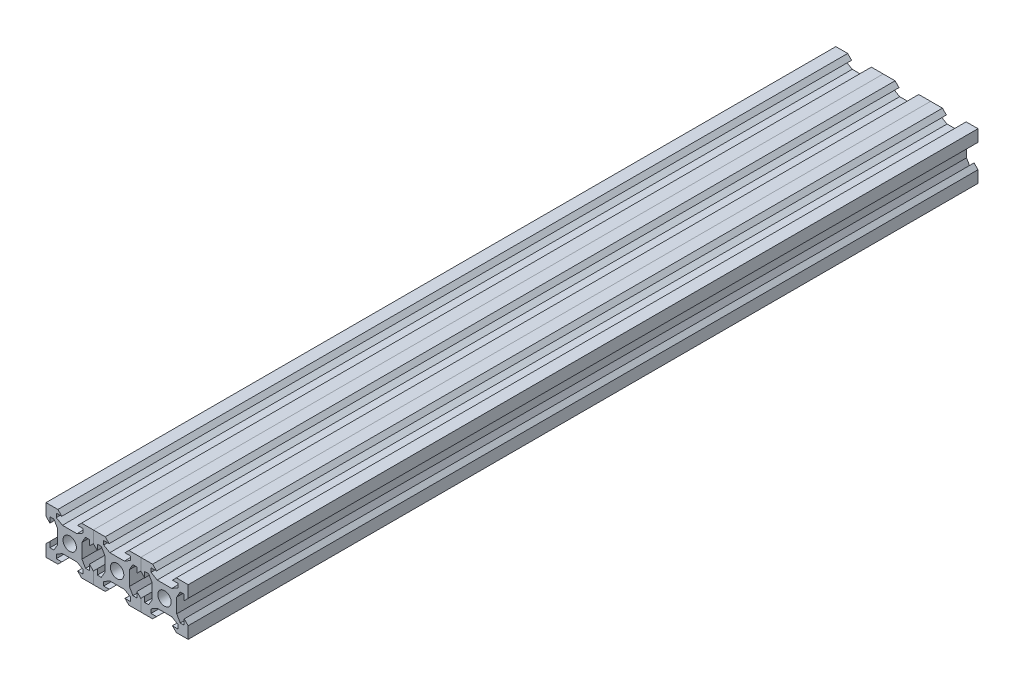
SolidWorks part; units mm, degrees
ref_plane "Alzado" through (0, 0, 0) normal (0, 0, 1) x (1, 0, 0)
ref_plane "Planta" through (0, 0, 0) normal (0, 1, 0) x (1, 0, 0)
ref_plane "Vista lateral" through (0, 0, 0) normal (1, 0, 0) x (0, 0, -1)
sketch "Sketch1" plane through (0, 0, 0) normal (0, 0, 1) x (1, 0, 0)
  line L0 (0, 0) -> (0, 50000) construction
  line L1 (45, 15) -> (-45, 15)
  line L2 (45, 15) -> (45, 7.5)
  line L3 (-45, -15) -> (-37.5, -15)
  line L4 (-45, 15) -> (-45, 7.5)
  line L5 (45, 15) -> (-45, -15) construction
  line L6 (45, -15) -> (-45, 15) construction
  line L7 (-45, -15) -> (-45, -7.5)
  line L8 (-22.5, -15) -> (-7.5, -15)
  line L9 (7.5, -15) -> (22.5, -15)
  line L10 (37.5, -15) -> (45, -15)
  line L11 (0, 0) -> (50000, 0) construction
  line L12 (30, 0) -> (30, 50000) construction
  line L13 (-30, 0) -> (-30, -50000) construction
  line L14 (-15, 7.5) -> (-15, 50007.5) construction
  line L15 (15, 7.5) -> (15, 50007.5) construction
  line L17 (45, -7.5) -> (45, -15)
  circle A0 centre (0, 0) radius 4.25
  circle A1 centre (-30, 0) radius 4.25
  circle A2 centre (30, 0) radius 4.25
  point P0 (0, 0)
  line B0 (42.5, 5) -> (42.5, 8.5)
  line B1 (42.5, 8.5) -> (40, 8.5)
  line B2 (40, 8.5) -> (37.75, 4.6029)
  line B3 (37.75, 4.6029) -> (37.75, -4.6029)
  line B4 (37.75, 0) -> (45, 0) construction
  line B5 (42.5, 5) -> (45, 7.5)
  line B6 (42.5, -5) -> (45, -7.5)
  line B7 (40, -8.5) -> (37.75, -4.6029)
  line B8 (42.5, -8.5) -> (40, -8.5)
  line B9 (42.5, -5) -> (42.5, -8.5)
  line B10 (35, -12.5) -> (38.5, -12.5)
  line B11 (38.5, -12.5) -> (38.5, -10)
  line B12 (38.5, -10) -> (34.6029, -7.75)
  line B13 (34.6029, -7.75) -> (25.3971, -7.75)
  line B14 (30, -7.75) -> (30, -15) construction
  line B15 (35, -12.5) -> (37.5, -15)
  line B16 (25, -12.5) -> (22.5, -15)
  line B17 (21.5, -10) -> (25.3971, -7.75)
  line B18 (21.5, -12.5) -> (21.5, -10)
  line B19 (25, -12.5) -> (21.5, -12.5)
  line B20 (-35, -12.5) -> (-38.5, -12.5)
  line B21 (-38.5, -12.5) -> (-38.5, -10)
  line B22 (-38.5, -10) -> (-34.6029, -7.75)
  line B23 (-34.6029, -7.75) -> (-25.3971, -7.75)
  line B24 (-30, -7.75) -> (-30, -15) construction
  line B25 (-35, -12.5) -> (-37.5, -15)
  line B26 (-25, -12.5) -> (-22.5, -15)
  line B27 (-21.5, -10) -> (-25.3971, -7.75)
  line B28 (-21.5, -12.5) -> (-21.5, -10)
  line B29 (-25, -12.5) -> (-21.5, -12.5)
  line B30 (5, -12.5) -> (8.5, -12.5)
  line B31 (8.5, -12.5) -> (8.5, -10)
  line B32 (8.5, -10) -> (4.6029, -7.75)
  line B33 (4.6029, -7.75) -> (-4.6029, -7.75)
  line B34 (0, -7.75) -> (0, -15) construction
  line B35 (5, -12.5) -> (7.5, -15)
  line B36 (-5, -12.5) -> (-7.5, -15)
  line B37 (-8.5, -10) -> (-4.6029, -7.75)
  line B38 (-8.5, -12.5) -> (-8.5, -10)
  line B39 (-5, -12.5) -> (-8.5, -12.5)
  line B40 (-42.5, 5) -> (-42.5, 8.5)
  line B41 (-42.5, 8.5) -> (-40, 8.5)
  line B42 (-40, 8.5) -> (-37.75, 4.6029)
  line B43 (-37.75, 4.6029) -> (-37.75, -4.6029)
  line B44 (-37.75, 0) -> (-45, 0) construction
  line B45 (-42.5, 5) -> (-45, 7.5)
  line B46 (-42.5, -5) -> (-45, -7.5)
  line B47 (-40, -8.5) -> (-37.75, -4.6029)
  line B48 (-42.5, -8.5) -> (-40, -8.5)
  line B49 (-42.5, -5) -> (-42.5, -8.5)
  line B50 (-35, 12.5) -> (-38.5, 12.5)
  line B51 (-38.5, 12.5) -> (-38.5, 10)
  line B52 (-38.5, 10) -> (-34.6029, 7.75)
  line B53 (-34.6029, 7.75) -> (-25.3971, 7.75)
  line B54 (-30, 7.75) -> (-30, 15) construction
  line B55 (-35, 12.5) -> (-37.5, 15)
  line B56 (-25, 12.5) -> (-22.5, 15)
  line B57 (-21.5, 10) -> (-25.3971, 7.75)
  line B58 (-21.5, 12.5) -> (-21.5, 10)
  line B59 (-25, 12.5) -> (-21.5, 12.5)
  line B60 (35, 12.5) -> (38.5, 12.5)
  line B61 (38.5, 12.5) -> (38.5, 10)
  line B62 (38.5, 10) -> (34.6029, 7.75)
  line B63 (34.6029, 7.75) -> (25.3971, 7.75)
  line B64 (30, 7.75) -> (30, 15) construction
  line B65 (35, 12.5) -> (37.5, 15)
  line B66 (25, 12.5) -> (22.5, 15)
  line B67 (21.5, 10) -> (25.3971, 7.75)
  line B68 (21.5, 12.5) -> (21.5, 10)
  line B69 (25, 12.5) -> (21.5, 12.5)
  line B70 (5, 12.5) -> (8.5, 12.5)
  line B71 (8.5, 12.5) -> (8.5, 10)
  line B72 (8.5, 10) -> (4.6029, 7.75)
  line B73 (4.6029, 7.75) -> (-4.6029, 7.75)
  line B74 (0, 7.75) -> (0, 15) construction
  line B75 (5, 12.5) -> (7.5, 15)
  line B76 (-5, 12.5) -> (-7.5, 15)
  line B77 (-8.5, 10) -> (-4.6029, 7.75)
  line B78 (-8.5, 12.5) -> (-8.5, 10)
  line B79 (-5, 12.5) -> (-8.5, 12.5)
  line B80 (17.5, 5) -> (17.5, 8.5)
  line B81 (17.5, 8.5) -> (20, 8.5)
  line B82 (20, 8.5) -> (22.25, 4.6029)
  line B83 (22.25, 4.6029) -> (22.25, -4.6029)
  line B84 (22.25, 0) -> (15, 0) construction
  line B85 (17.5, 5) -> (15, 7.5)
  line B86 (17.5, -5) -> (15, -7.5)
  line B87 (20, -8.5) -> (22.25, -4.6029)
  line B88 (17.5, -8.5) -> (20, -8.5)
  line B89 (17.5, -5) -> (17.5, -8.5)
  line B90 (-17.5, 5) -> (-17.5, 8.5)
  line B91 (-17.5, 8.5) -> (-20, 8.5)
  line B92 (-20, 8.5) -> (-22.25, 4.6029)
  line B93 (-22.25, 4.6029) -> (-22.25, -4.6029)
  line B94 (-22.25, 0) -> (-15, 0) construction
  line B95 (-17.5, 5) -> (-15, 7.5)
  line B96 (-17.5, -5) -> (-15, -7.5)
  line B97 (-20, -8.5) -> (-22.25, -4.6029)
  line B98 (-17.5, -8.5) -> (-20, -8.5)
  line B99 (-17.5, -5) -> (-17.5, -8.5)
  line B100 (-12.5, 5) -> (-12.5, 8.5)
  line B101 (-12.5, 8.5) -> (-10, 8.5)
  line B102 (-10, 8.5) -> (-7.75, 4.6029)
  line B103 (-7.75, 4.6029) -> (-7.75, -4.6029)
  line B104 (-7.75, 0) -> (-15, 0) construction
  line B105 (-12.5, 5) -> (-15, 7.5)
  line B106 (-12.5, -5) -> (-15, -7.5)
  line B107 (-10, -8.5) -> (-7.75, -4.6029)
  line B108 (-12.5, -8.5) -> (-10, -8.5)
  line B109 (-12.5, -5) -> (-12.5, -8.5)
  line B110 (12.5, 5) -> (12.5, 8.5)
  line B111 (12.5, 8.5) -> (10, 8.5)
  line B112 (10, 8.5) -> (7.75, 4.6029)
  line B113 (7.75, 4.6029) -> (7.75, -4.6029)
  line B114 (7.75, 0) -> (15, 0) construction
  line B115 (12.5, 5) -> (15, 7.5)
  line B116 (12.5, -5) -> (15, -7.5)
  line B117 (10, -8.5) -> (7.75, -4.6029)
  line B118 (12.5, -8.5) -> (10, -8.5)
  line B119 (12.5, -5) -> (12.5, -8.5)
  dimension "D3" = 8.5
  dimension "D4" = 15
  dimension "D5" = 30
  dimension "D1" = 90
  dimension "D2" = 30
sketch_block_instance "Block1-1"
sketch_block "Block1" parameters "D1"=45, "D2"=60, "D3"=10, "D4"=3.5, "D5"=2.5, "D6"=4.5
sketch_block_instance "Block1-2"
sketch_block_instance "Block1-3"
sketch_block_instance "Block1-4"
sketch_block_instance "Block1-5"
sketch_block_instance "Block1-9"
sketch_block_instance "Block1-10"
sketch_block_instance "Block1-11"
sketch_block_instance "Block1-12"
sketch_block_instance "Block1-13"
sketch_block_instance "Block1-14"
sketch_block_instance "Block1-15"
extrude "Boss-Extrude1" add sketch "Sketch1" along normal mid plane 500 contours B49 B46 L7 L3 B25 B20 B21 B22 B23 B27 B28 B29 B26 L8 B36 B39 B38 B37 B33 B32 B31 B30 B35 L9 B16 B19 B18 B17 B13 B12 B11 B10 B15 L10 L17 B6 B9 B8 B7 B3 B2 B1 B0 B5 L2 L1 L4 B45 B40 B41 B42
ref_plane "Plane1" through (-15, 0, 0) normal (-1, 0, 0) x (0, 0, 1)
ref_plane "Plane2" through (15, 0, 0) normal (-1, 0, 0) x (0, 0, 1)
split line "Split Line1"
